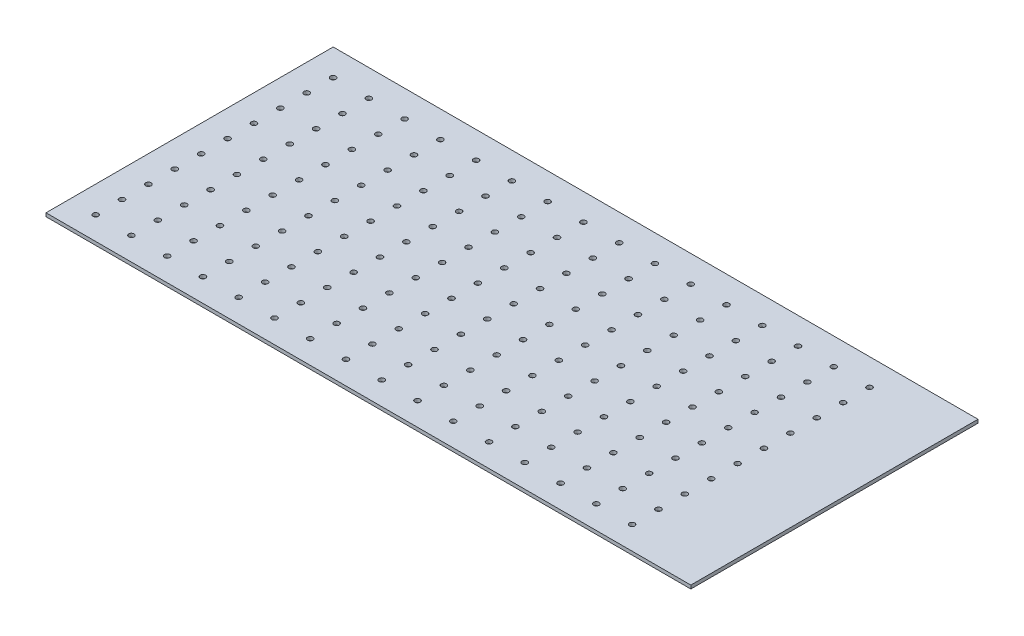
SolidWorks part; units mm, degrees
ref_plane "Front Plane" through (0, 0, 0) normal (0, 0, 1) x (1, 0, 0)
ref_plane "Top Plane" through (0, 0, 0) normal (0, 1, 0) x (1, 0, 0)
ref_plane "Right Plane" through (0, 0, 0) normal (1, 0, 0) x (0, 0, -1)
sketch "Sketch1" plane through (0, 0, 0) normal (0, 1, 0) x (1, 0, 0)
  line L1 (-272.5, 132.5) -> (272.5, 132.5)
  line L2 (-272.5, 132.5) -> (-272.5, -132.5)
  line L3 (-272.5, -132.5) -> (272.5, -132.5)
  line L4 (272.5, 132.5) -> (272.5, -132.5)
  line L5 (-272.5, 132.5) -> (272.5, -132.5) construction
  line L6 (-272.5, -132.5) -> (272.5, 132.5) construction
  point P0 (0, 0)
  dimension "D1" = 265
  dimension "D2" = 545
extrude "Boss-Extrude1" add sketch "Sketch1" along normal blind 3.18
sketch "Sketch4" plane through (0, 3.18, 0) normal (0, 1, 0) x (1, 0, 0)
  line L0 (272.5, 132.5) -> (-272.5, 132.5) construction
  line L1 (-272.5, 132.5) -> (-272.5, -132.5) construction
  circle A0 centre (-248, 107.9) radius 2.5
  dimension "D1" = 24.6
  dimension "D2" = 24.5
  dimension "D3" = 5
extrude "Cut-Extrude1" cut sketch "Sketch4" against normal up to next contours A0
pattern_linear "LPattern1" count 16 spacing 33 along (1, 0, 0) count 10 spacing 24.3429 along (0, 0, 1) of "Cut-Extrude1"
sketch "Sketch7" plane through (272.5, 0, 0) normal (1, 0, 0) x (0, 0, -1)
  line L1 (-132.5, 3.18) -> (132.5, 3.18)
  line L2 (-132.5, 3.18) -> (-132.5, 0)
  line L3 (-132.5, 0) -> (132.5, 0)
  line L4 (132.5, 3.18) -> (132.5, 0)
extrude "Boss-Extrude3" add sketch "Sketch7" along normal blind 50
